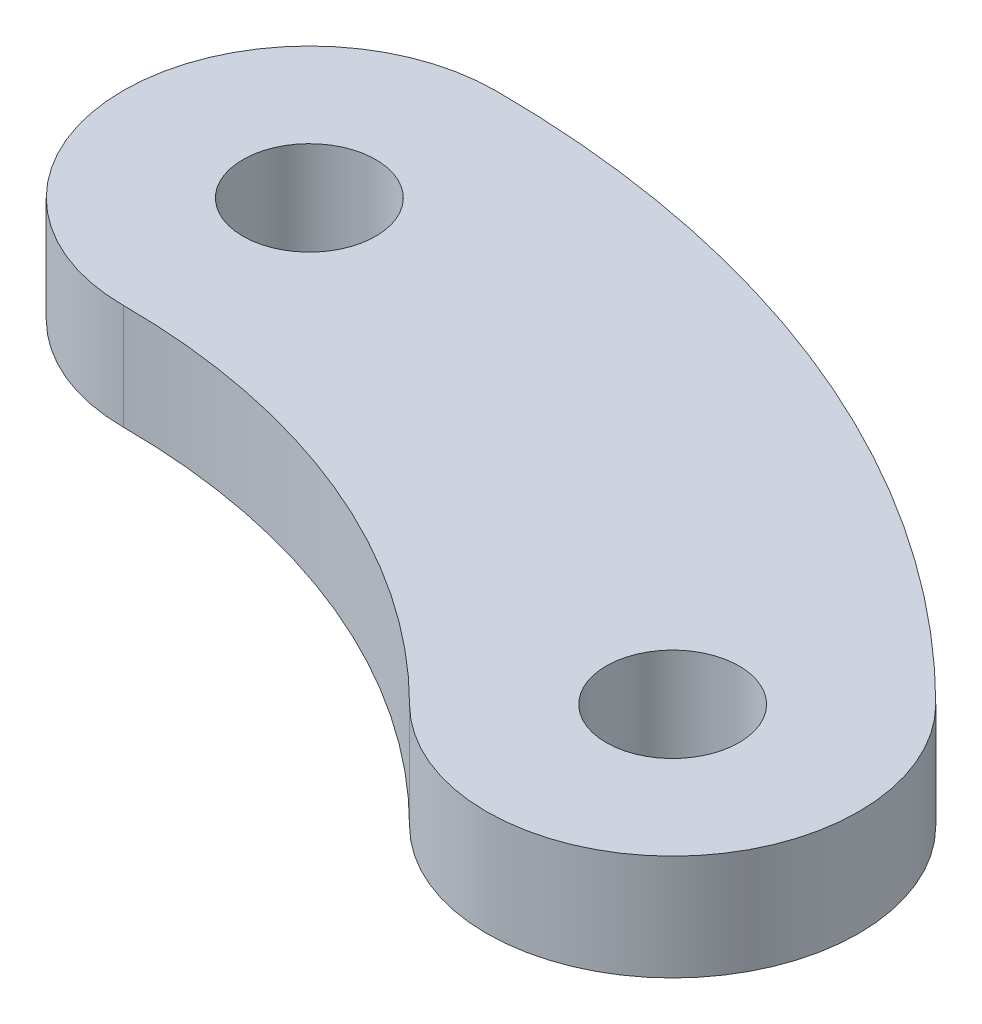
SolidWorks part; units mm, degrees
ref_plane "Front Plane" through (0, 0, 0) normal (0, 0, 1) x (1, 0, 0)
ref_plane "Top Plane" through (0, 0, 0) normal (0, 1, 0) x (1, 0, 0)
ref_plane "Right Plane" through (0, 0, 0) normal (1, 0, 0) x (0, 0, -1)
sketch "Sketch1" plane through (0, 0, 0) normal (0, 1, 0) x (1, 0, 0)
  line L0 (0, 66) -> (0, 0) construction
  line L1 (0, 0) -> (46.669, 46.669) construction
  arc A0 (0, 66) -> (46.669, 46.669) centre (0, 0) cw construction
  arc A1 (56.5685, 56.5685) -> (0, 80) centre (0, 0) ccw
  arc A2 (36.7696, 36.7696) -> (0, 52) centre (0, 0) ccw
  arc A3 (36.7696, 36.7696) -> (56.5685, 56.5685) centre (46.669, 46.669) ccw
  arc A4 (0, 80) -> (0, 52) centre (0, 66) ccw
  circle A5 centre (0, 66) radius 5
  circle A6 centre (46.669, 46.669) radius 5
  point P4 (25.2571, 60.976)
  point P15 (0, 0)
  point P16 (46.669, 46.669)
  dimension "D2" = 52
  dimension "D3" = 80
  dimension "D1" = 45
extrude "Boss-Extrude1" add sketch "Sketch1" along normal blind 7.9375
